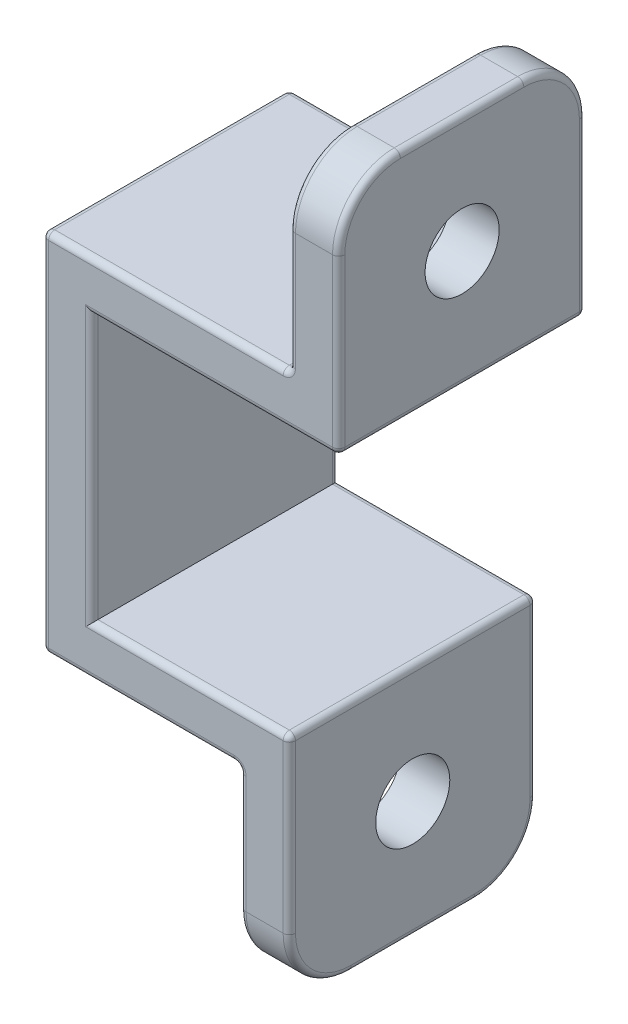
SolidWorks part; units mm, degrees
ref_plane "Front Plane" through (0, 0, 0) normal (0, 0, 1) x (1, 0, 0)
ref_plane "Top Plane" through (0, 0, 0) normal (0, 1, 0) x (1, 0, 0)
ref_plane "Right Plane" through (0, 0, 0) normal (1, 0, 0) x (0, 0, -1)
sketch "Sketch2" plane through (0, 0, 0) normal (1, 0, 0) x (0, 0, -1)
  line L1 (-10, -14.8) -> (10, -14.8)
  line L2 (-10, -14.8) -> (-10, 14.8)
  line L3 (-10, 14.8) -> (10, 14.8)
  line L4 (10, -14.8) -> (10, 14.8)
  line L5 (-10, -14.8) -> (10, 14.8) construction
  line L6 (-10, 14.8) -> (10, -14.8) construction
  point P0 (0, 0)
  dimension "D1" = 29.6
  dimension "D2" = 20
extrude "Boss-Extrude1" add sketch "Sketch2" along normal blind 4
sketch "Sketch3" plane through (4, 0, 0) normal (1, 0, 0) x (0, 0, -1)
  line L0 (10, -14.8) -> (10, 14.8) construction
  line L1 (-10, 14.8) -> (10, 14.8)
  line L2 (-10, 14.8) -> (-10, 10.8)
  line L3 (-10, 10.8) -> (10, 10.8)
  line L4 (10, 14.8) -> (10, 10.8)
  dimension "D1" = 4
extrude "Boss-Extrude2" add sketch "Sketch3" along normal blind 20
sketch "Sketch4" plane through (4, 0, 0) normal (1, 0, 0) x (0, 0, -1)
  line L0 (10, -14.8) -> (10, 10.8) construction
  line L1 (-10, -14.8) -> (10, -14.8)
  line L2 (-10, -14.8) -> (-10, -10.8)
  line L3 (-10, -10.8) -> (10, -10.8)
  line L4 (10, -14.8) -> (10, -10.8)
  dimension "D1" = 4
extrude "Boss-Extrude3" add sketch "Sketch4" along normal blind 16
sketch "Sketch5" plane through (0, 14.8, 0) normal (0, 1, 0) x (1, 0, 0)
  line L0 (24, -10) -> (0, -10) construction
  line L1 (24, 10) -> (20, 10)
  line L2 (24, 10) -> (24, -10)
  line L3 (24, -10) -> (20, -10)
  line L4 (20, 10) -> (20, -10)
  dimension "D1" = 4
extrude "Boss-Extrude4" add sketch "Sketch5" along normal blind 15
sketch "Sketch6" plane through (0, -14.8, 0) normal (0, -1, 0) x (1, 0, 0)
  line L0 (20, -10) -> (0, -10) construction
  line L1 (20, 10) -> (16, 10)
  line L2 (20, 10) -> (20, -10)
  line L3 (20, -10) -> (16, -10)
  line L4 (16, 10) -> (16, -10)
  dimension "D1" = 4
extrude "Boss-Extrude5" add sketch "Sketch6" along normal blind 15
fillet "Fillet1" radius 5 4 edges at (18, -29.8, 10) (18, -29.8, -10) (22, 29.8, -10) (22, 29.8, 10)
fillet "Fillet3" radius 0.5 38 edges at (24, 28.3355, -8.5355) (20, 28.3355, -8.5355) (24, 29.8, 0) (20, 28.3355, 8.5355) (24, 28.3355, 8.5355) (20, -28.3355, -8.5355) (20, -29.8, 0) (20, -28.3355, 8.5355) (20, 29.8, 0) (0, 14.8, 0) (20, 14.8, 0) (16, -28.3355, -8.5355) (16, -28.3355, 8.5355) (16, -29.8, 0) (0, -14.8, 0) (16, -14.8, 0) (12, -10.8, -10) (4, 0, -10) (14, 10.8, -10) (24, 17.8, -10) (20, 19.8, -10) (10, 14.8, -10) (0, 0, -10) (8, -14.8, -10) (16, -19.8, -10) (20, -17.8, -10) (8, -14.8, 10) (0, 0, 10) (10, 14.8, 10) (20, 19.8, 10) (24, 17.8, 10) (14, 10.8, 10) (4, 0, 10) (12, -10.8, 10) (20, -17.8, 10) (16, -19.8, 10) (20, -10.8, 0) (24, 10.8, 0)
sketch "Sketch9" plane through (24, 0, 0) normal (1, 0, 0) x (0, 0, -1)
  line L0 (0, 29.3) -> (0, 11.3) construction
  line L1 (5, 29.3) -> (-5, 29.3) construction
  line L2 (-9.5, 11.3) -> (9.5, 11.3) construction
  circle A0 centre (0, 20.3) radius 3
  point P6 (0, 20.3)
  dimension "D1" = 6
extrude "Cut-Extrude2" cut sketch "Sketch9" against normal up to next
sketch "Sketch10" plane through (20, 0, 0) normal (1, 0, 0) x (0, 0, -1)
  line L0 (0, -11.3) -> (0, -29.3) construction
  line L1 (9.5, -11.3) -> (-9.5, -11.3) construction
  line L2 (-5, -29.3) -> (5, -29.3) construction
  circle A0 centre (0, -20.3) radius 3
  point P6 (0, -20.3)
  dimension "D1" = 6
extrude "Cut-Extrude3" cut sketch "Sketch10" against normal up to next
equation "\"width\"= 20"
equation "\"handle_thickness\"= 4"
equation "\"handle_tolerance\"= 0.1"
equation "\"D1@Sketch2\"=19.4mm+(\"handle_thickness\"+\"handle_tolerance\"+\"antenna_thickness\")*2"
equation "\"D2@Sketch2\"=\"width\""
equation "\"D1@Boss-Extrude1\"=\"handle_thickness\""
equation "\"D1@Sketch3\"=\"handle_thickness\""
equation "\"D1@Sketch4\"=\"handle_thickness\""
equation "\"D1@Boss-Extrude3\"=19-4+\"antenna_thickness\""
equation "\"D1@Sketch5\"=\"handle_thickness\""
equation "\"D1@Sketch6\"=\"handle_thickness\""
equation "\"antenna_thickness\"= 1"
